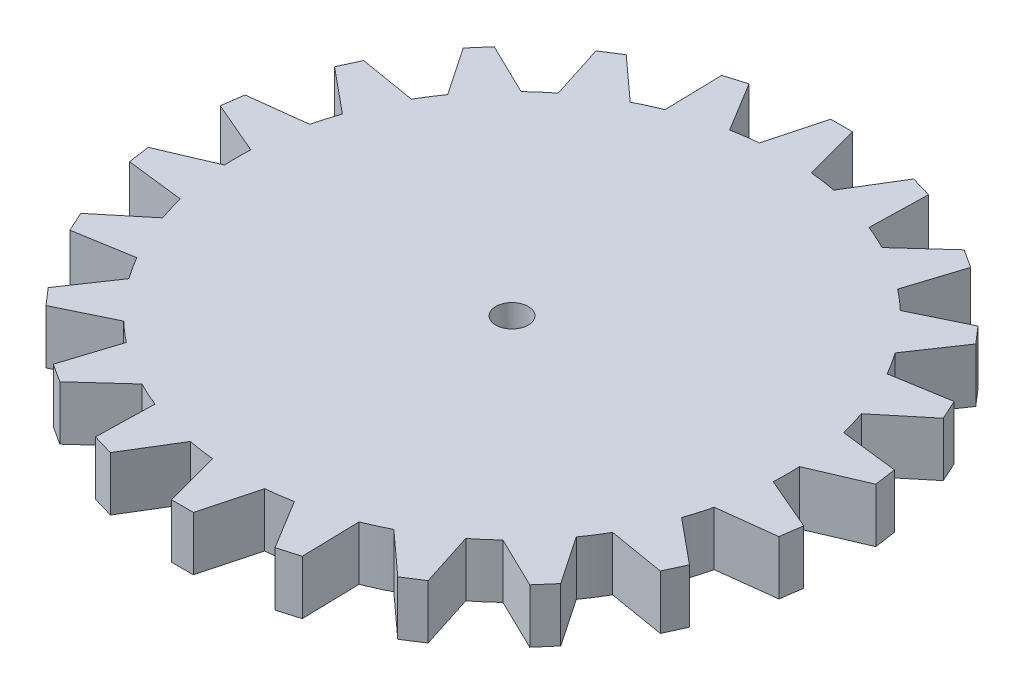
SolidWorks part; units mm, degrees
ref_plane "Front Plane" through (0, 0, 0) normal (0, 0, 1) x (1, 0, 0)
ref_plane "Top Plane" through (0, 0, 0) normal (0, 1, 0) x (1, 0, 0)
ref_plane "Right Plane" through (0, 0, 0) normal (1, 0, 0) x (0, 0, -1)
sketch "Sketch1" plane through (0, 0, 0) normal (0, 1, 0) x (1, 0, 0)
  circle A0 centre (0, 0) radius 12.7
  dimension "D1" = 25.4
extrude "Boss-Extrude1" add sketch "Sketch1" along normal blind 2.5
sketch "Sketch2" plane through (0, 2.5, 0) normal (0, 1, 0) x (1, 0, 0)
  line L0 (0, 0) -> (0, 15.24) construction
  line L1 (-1.3247, 12.192) -> (1.3247, 12.192)
  line L2 (-0.508, 15.24) -> (0.508, 15.24)
  line L3 (0, 0) -> (12.7, 0) construction
  line L4 (-1.3247, 12.192) -> (-0.508, 15.24)
  line L5 (0.508, 15.24) -> (1.3247, 12.192)
  circle A0 centre (0, 0) radius 12.7 construction
  point P11 (0, 15.24)
  point P12 (0, 12.192)
  dimension "D1" = 12.192
  dimension "D2" = 15.24
  dimension "D3" = 75
  dimension "D4" = 1.016
extrude "Boss-Extrude2" add sketch "Sketch2" against normal blind 2.5
pattern_circular "CirPattern1" count 22 over 360 about axis through (0, 0, 0) along (0, 1, 0) of "Boss-Extrude2"
sketch "Sketch3" plane through (0, 2.5, 0) normal (0, 1, 0) x (1, 0, 0)
  circle A0 centre (0, 0) radius 0.75
  dimension "D1" = 1.5
extrude "Cut-Extrude1" cut sketch "Sketch3" against normal blind 5
